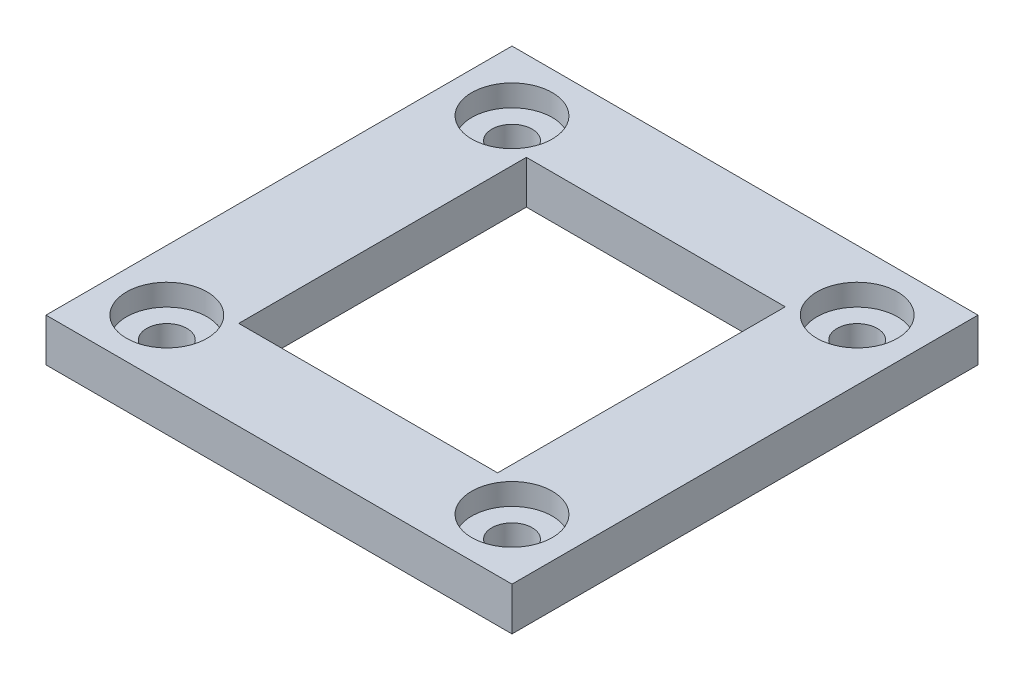
SolidWorks part; units mm, degrees
ref_plane "Front Plane" through (0, 0, 0) normal (0, 0, 1) x (1, 0, 0)
ref_plane "Top Plane" through (0, 0, 0) normal (0, 1, 0) x (1, 0, 0)
ref_plane "Right Plane" through (0, 0, 0) normal (1, 0, 0) x (0, 0, -1)
sketch "Sketch1" plane through (0, 0, 0) normal (0, 1, 0) x (1, 0, 0)
  line L1 (0, 0) -> (32.4, 0)
  line L2 (0, 0) -> (0, 32.4)
  line L3 (0, 32.4) -> (32.4, 32.4)
  line L4 (32.4, 0) -> (32.4, 32.4)
  dimension "D1" = 32.4
  dimension "D2" = 32.4
extrude "Boss-Extrude1" add sketch "Sketch1" along normal blind 3
hole_wizard "CBORE for M1.6 SHCS1" positions "Sketch3" profile "Sketch4" counterbore size "M1.6" standard "ANSI Metric" end condition through all
sketch "Sketch3" plane through (0, 3, 0) normal (0, 1, 0) x (1, 0, 0)
  line L0 (4.2, 28.2) -> (4.2, 4.2) construction
  line L1 (4.2, 4.2) -> (28.2, 4.2) construction
  line L2 (28.2, 4.2) -> (28.2, 28.2) construction
  line L3 (28.2, 28.2) -> (4.2, 28.2) construction
  line L11 (4.2, 4.2) -> (4.2, 0) construction
  line L15 (28.2, 28.2) -> (28.2, 32.4) construction
  line L16 (0, 0) -> (32.4, 0) construction
  line L17 (32.4, 32.4) -> (0, 32.4) construction
  line L18 (4.2, 0) -> (0, 0) construction
  line L20 (28.2, 32.4) -> (32.4, 32.4) construction
  point P0 (4.2, 28.2)
  point P2 (28.2, 28.2)
  point P4 (28.2, 4.2)
  point P6 (4.2, 4.2)
  dimension "D1" = 24
  dimension "D2" = 24
sketch "Sketch4" plane through (4.2, 3, -28.2) normal (1, 0, 0) x (0, 0, 1)
  line L0 (0, 0) -> (0, 3)
  line L1 (0, 3) -> (1.4, 3)
  line L3 (1.4, 3) -> (1.4, 1.5)
  line L4 (1.4, 1.5) -> (2.8, 1.5)
  line L5 (2.8, 1.5) -> (2.8, 0)
  line L7 (2.8, 0) -> (0, 0)
  line L11 (0, -6.35) -> (0, 107.95) construction
  dimension "Thru Hole Dia." = 2.8
  dimension "Thru Hole Depth" = 3
  dimension "C'Bore Dia." = 5.6
  dimension "C'Bore Depth" = 1.5
sketch "Sketch5" plane through (0, 3, 0) normal (0, 1, 0) x (1, 0, 0)
  line L0 (7.2, 0) -> (0, 0) construction
  line L1 (32.4, 0) -> (32.4, 32.4) construction
  line L2 (25.2, 26.2) -> (32.4, 26.2) construction
  line L5 (25.2, 6.2) -> (7.2, 6.2)
  line L6 (25.2, 6.2) -> (25.2, 26.2)
  line L7 (25.2, 26.2) -> (7.2, 26.2)
  line L8 (7.2, 6.2) -> (7.2, 26.2)
  line L10 (7.2, 6.2) -> (7.2, 0) construction
  line L11 (0, 0) -> (32.4, 0) construction
  line L12 (7.2, 26.2) -> (7.2, 32.4) construction
  line L13 (32.4, 32.4) -> (0, 32.4) construction
  dimension "D1" = 20
  dimension "D2" = 18
extrude "Cut-Extrude1" cut sketch "Sketch5" against normal through all contours L8 L5 L6 L7
